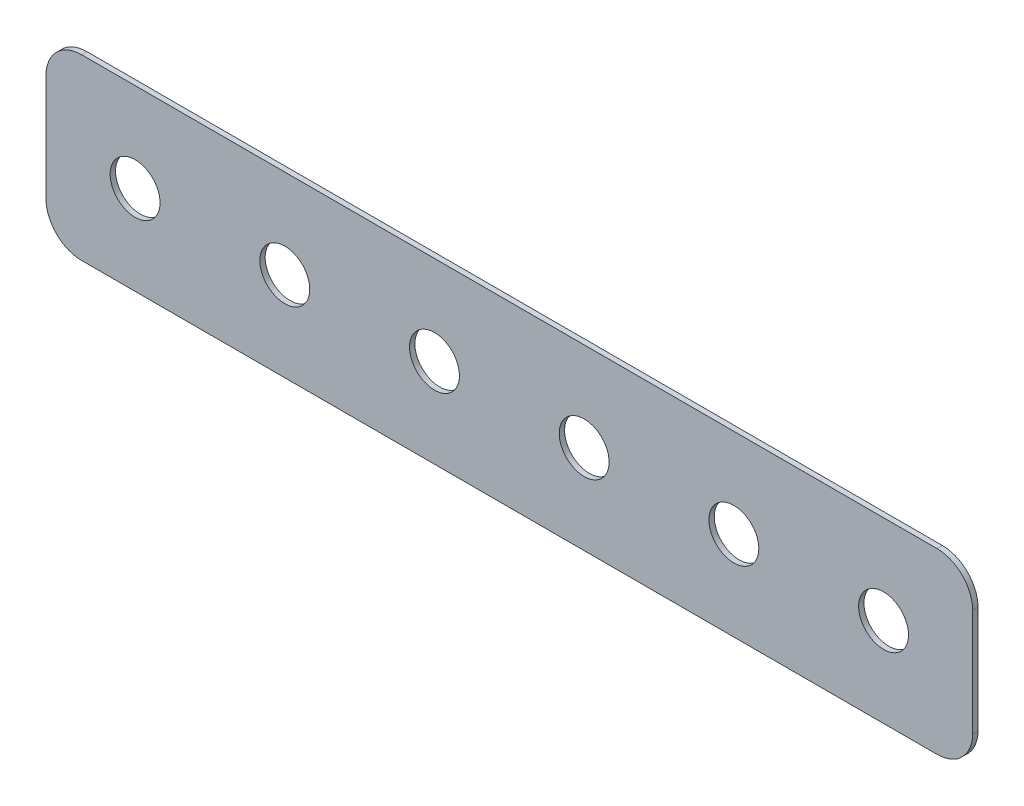
SolidWorks part; units mm, degrees
ref_plane "Front Plane" through (0, 0, 0) normal (0, 0, 1) x (1, 0, 0)
ref_plane "Top Plane" through (0, 0, 0) normal (0, 1, 0) x (1, 0, 0)
ref_plane "Right Plane" through (0, 0, 0) normal (1, 0, 0) x (0, 0, -1)
sketch "Sketch1" plane through (0, 0, 0) normal (0, 0, 1) x (1, 0, 0)
  line L1 (-1651, -317.5) -> (1651, -317.5)
  line L2 (-1651, -317.5) -> (-1651, 317.5)
  line L3 (-1651, 317.5) -> (1651, 317.5)
  line L4 (1651, -317.5) -> (1651, 317.5)
  line L5 (-1651, -317.5) -> (1651, 317.5) construction
  line L6 (-1651, 317.5) -> (1651, -317.5) construction
  point P0 (0, 0)
  dimension "D1" = 3302
  dimension "D2" = 635
extrude "Boss-Extrude1" add sketch "Sketch1" along normal blind 19.05
sketch "Sketch2" plane through (0, 0, 19.05) normal (0, 0, 1) x (1, 0, 0)
  line L0 (-1651, 317.5) -> (-1651, -317.5) construction
  line L1 (1651, -317.5) -> (1651, 317.5) construction
  circle A0 centre (-1333.5, 0) radius 88.9
  circle A1 centre (-800.1, 0) radius 88.9
  circle A2 centre (-266.7, 0) radius 88.9
  circle A3 centre (266.7, 0) radius 88.9
  circle A4 centre (800.1, 0) radius 88.9
  circle A5 centre (1333.5, 0) radius 88.9
  dimension "D1" = 177.8
  dimension "D2" = 317.5
  dimension "D4" = 317.5
  dimension "D3" = 6
extrude "Cut-Extrude1" cut sketch "Sketch2" against normal through all
fillet "Fillet1" radius 127 4 edges at (-1651, 317.5, 9.525) (-1651, -317.5, 9.525) (1651, -317.5, 9.525) (1651, 317.5, 9.525)
